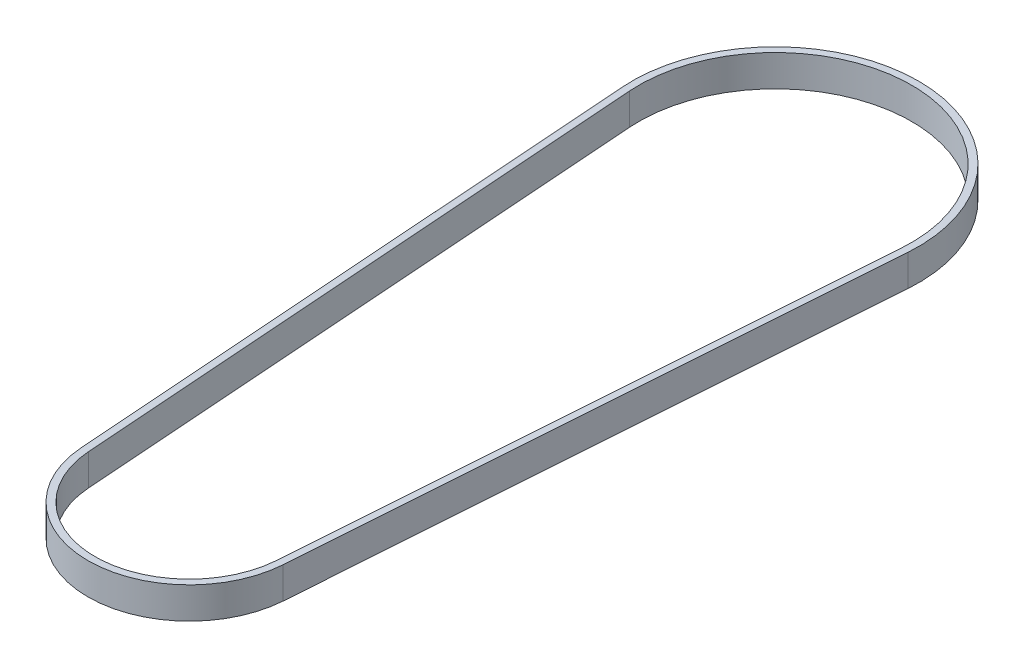
SolidWorks part; units mm, degrees
ref_plane "Front Plane" through (0, 0, 0) normal (0, 0, 1) x (1, 0, 0)
ref_plane "Top Plane" through (0, 0, 0) normal (0, 1, 0) x (1, 0, 0)
ref_plane "Right Plane" through (0, 0, 0) normal (1, 0, 0) x (0, 0, -1)
sketch "Sketch2" plane through (0, 0, 0) normal (0, 1, 0) x (1, 0, 0)
  line L0 (20.4474, -1.4676) -> (14.4628, -84.8481)
  line L1 (-20.4474, -1.4676) -> (-14.4628, -84.8481)
  line L2 (-19.45, -1.396) -> (-13.4654, -84.7765)
  line L3 (19.45, -1.396) -> (13.4654, -84.7765)
  arc A0 (20.4474, -1.4676) -> (-20.4474, -1.4676) centre (0, 0) ccw
  arc A1 (-14.4628, -84.8481) -> (14.4628, -84.8481) centre (0, -83.81) ccw
  arc A2 (19.45, -1.396) -> (-19.45, -1.396) centre (0, 0) ccw
  arc A3 (-13.4654, -84.7765) -> (13.4654, -84.7765) centre (0, -83.81) ccw
  point P1 (0, 0)
  dimension "D1" = 20.5
  dimension "D2" = 14.5
  dimension "D3" = 83.81
  dimension "D4" = 1
extrude "Boss-Extrude1" add sketch "Sketch2" along normal blind 4.5
